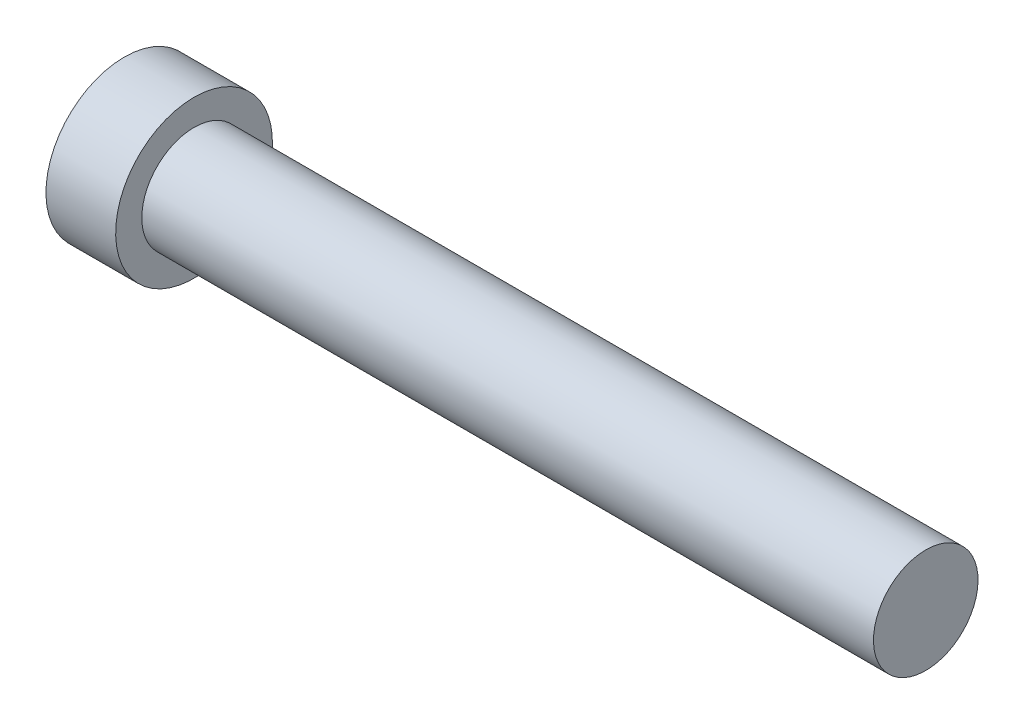
SolidWorks part; units mm, degrees
ref_plane "Front Plane" through (0, 0, 0) normal (0, 0, 1) x (1, 0, 0)
ref_plane "Top Plane" through (0, 0, 0) normal (0, 1, 0) x (1, 0, 0)
ref_plane "Right Plane" through (0, 0, 0) normal (1, 0, 0) x (0, 0, -1)
sketch "Sketch1" plane through (0, 0, 0) normal (0, 0, 1) x (1, 0, 0)
  line L0 (0, 0) -> (0, 22.5)
  line L1 (0, 22.5) -> (20, 22.5)
  line L2 (20, 22.5) -> (20, 15)
  line L3 (20, 15) -> (230, 15)
  line L4 (230, 15) -> (230, 0)
  line L5 (230, 0) -> (0, 0) construction
  line L6 (0, 0) -> (230, 0)
  dimension "D1" = 20
  dimension "D2" = 22.5
  dimension "D3" = 230
  dimension "D4" = 15
revolve "Revolve1" add sketch "Sketch1" angle 360 about L5
